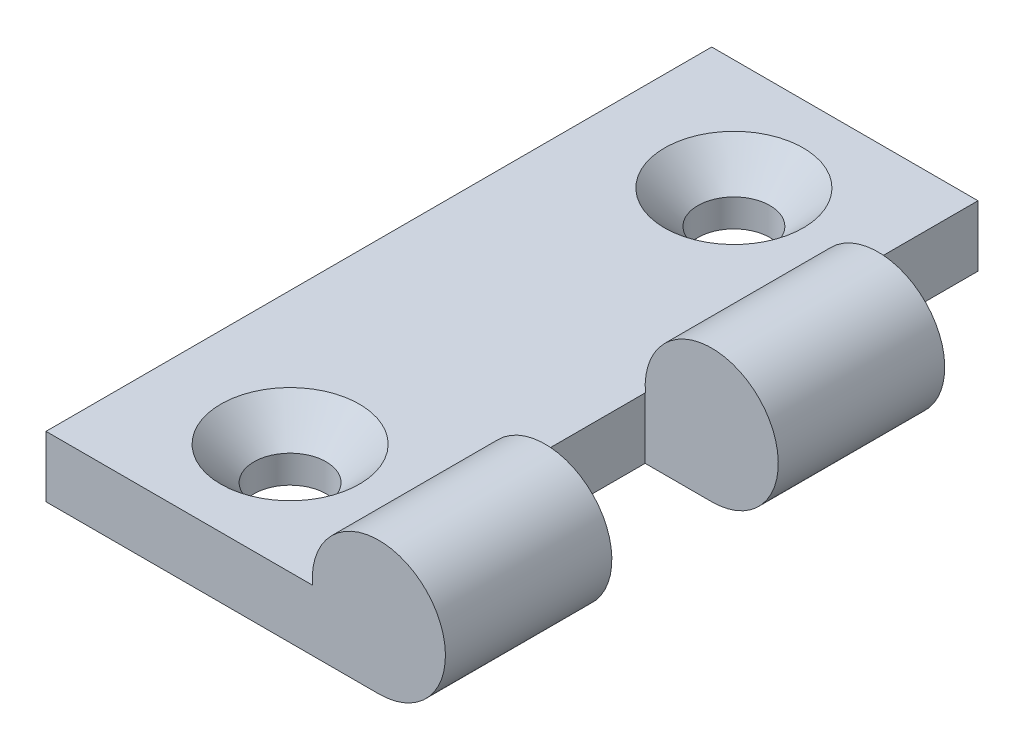
SolidWorks part; units mm, degrees
ref_plane "前视基准面" through (0, 0, 0) normal (0, 0, 1) x (1, 0, 0)
ref_plane "上视基准面" through (0, 0, 0) normal (0, 1, 0) x (1, 0, 0)
ref_plane "右视基准面" through (0, 0, 0) normal (1, 0, 0) x (0, 0, -1)
sketch "草图1" plane through (0, 0, 0) normal (0, 0, 1) x (1, 0, 0)
  line L0 (0, 0) -> (30, 0)
  line L1 (0, 0) -> (0, 5.5)
  line L2 (0, 5.5) -> (24.0209, 5.5)
  line L3 (30, 6) -> (30, 0) construction
  arc A0 (30, 0) -> (24.0209, 5.5) centre (30, 6) ccw
  dimension "D3" = 12
  dimension "D1" = 30
  dimension "D2" = 5.5
extrude "凸台-拉伸1" add sketch "草图1" against normal blind 60
sketch "草图2" plane through (0, 5.5, 0) normal (0, 1, 0) x (1, 0, 0)
  line L0 (36, 0) -> (36, 60) construction
  line L1 (24, 60) -> (36, 60)
  line L2 (24, 60) -> (24, 45)
  line L3 (24, 45) -> (36, 45)
  line L4 (36, 60) -> (36, 45)
  line L5 (24, 60) -> (24, 0) construction
  line L6 (24, 30) -> (36, 30)
  line L7 (24, 30) -> (24, 15)
  line L8 (24, 15) -> (36, 15)
  line L9 (36, 30) -> (36, 15)
  line L10 (24.0209, 0) -> (0, 0) construction
  point P13 (30, 15)
  dimension "D1" = 15
  dimension "D2" = 15
  dimension "D3" = 15
extrude "切除-拉伸1" cut sketch "草图2" against normal through all both and the other way through all
sketch "草图3" plane through (0, 5.5, 0) normal (0, 1, 0) x (1, 0, 0)
  line L0 (0, 30) -> (15.8009, 30) construction
  line L1 (0, 60) -> (0, 0) construction
  line L2 (12, 60) -> (12, 9.4628) construction
  line L3 (24, 60) -> (0, 60) construction
  line L4 (36, 45) -> (24, 45) construction
  line L5 (30, 45) -> (30, 0) construction
  circle A0 centre (12, 50) radius 3.25
  circle A1 centre (12, 10) radius 3.25
  dimension "D3" = 6.5
  dimension "D1" = 40
  dimension "D2" = 18
extrude "切除-拉伸2" cut sketch "草图3" against normal blind 10
chamfer "倒角1" distance 3 angle 45 2 edges at (12, 5.5, -13.25) (12, 5.5, -46.75)
